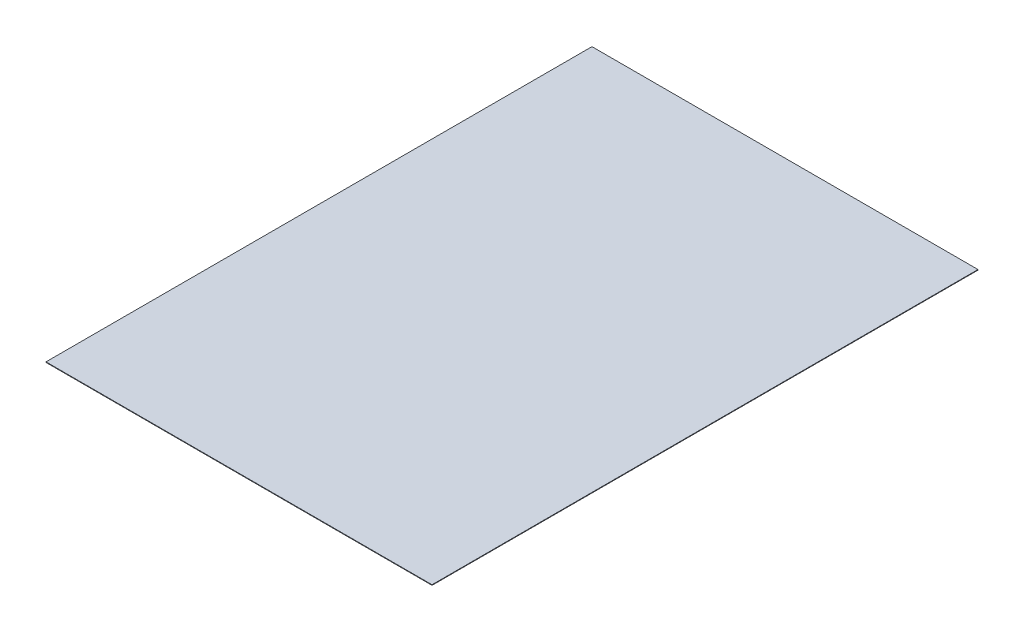
SolidWorks part; units mm, degrees
ref_plane "Front Plane" through (0, 0, 0) normal (0, 0, 1) x (1, 0, 0)
ref_plane "Top Plane" through (0, 0, 0) normal (0, 1, 0) x (1, 0, 0)
ref_plane "Right Plane" through (0, 0, 0) normal (1, 0, 0) x (0, 0, -1)
sketch "Sketch1" plane through (0, 0, 0) normal (0, 1, 0) x (1, 0, 0)
  line L1 (105, -148.5) -> (-105, -148.5)
  line L2 (105, -148.5) -> (105, 148.5)
  line L3 (105, 148.5) -> (-105, 148.5)
  line L4 (-105, -148.5) -> (-105, 148.5)
  line L5 (105, -148.5) -> (-105, 148.5) construction
  line L6 (105, 148.5) -> (-105, -148.5) construction
  point P0 (0, 0)
  dimension "D1" = 210
  dimension "D2" = 297
extrude "Boss-Extrude1" add sketch "Sketch1" along normal blind 0.3
